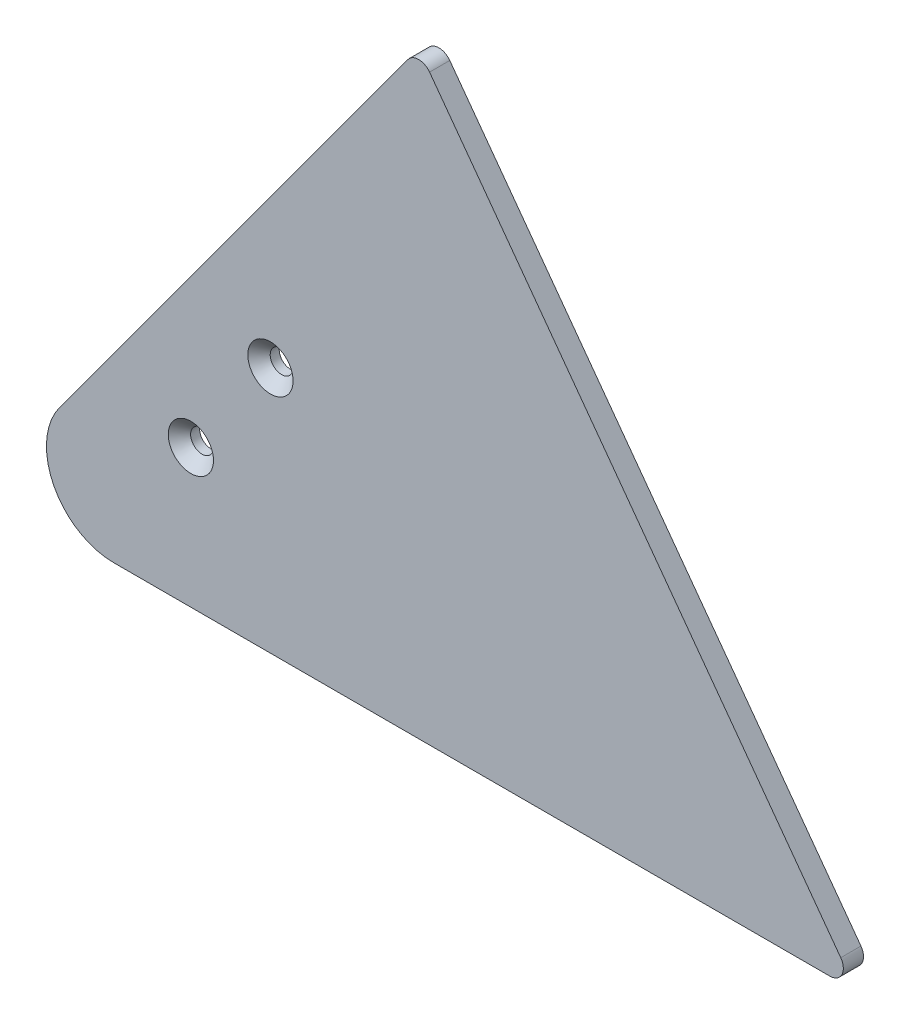
SolidWorks part; units mm, degrees
material "环氧树脂,未充填"
ref_plane "前视基准面" through (0, 0, 0) normal (0, 0, 1) x (1, 0, 0)
ref_plane "上视基准面" through (0, 0, 0) normal (0, 1, 0) x (1, 0, 0)
ref_plane "右视基准面" through (0, 0, 0) normal (1, 0, 0) x (0, 0, -1)
sketch "草图1" plane through (0, 0, 0) normal (0, 0, 1) x (1, 0, 0)
  line L0 (0, 0) -> (130, 0)
  line L1 (130, 0) -> (65, 88.7412)
  line L2 (65, 88.7412) -> (0, 0)
  dimension "D1" = 130
  dimension "D2" = 110
  dimension "D3" = 110
extrude "凸台-拉伸1" add sketch "草图1" along normal blind 3
sketch "草图2" plane through (0, 0, 3) normal (0, 0, 1) x (1, 0, 0)
  line L0 (73.0571, 77.7412) -> (16.1143, 0) construction
  line L1 (130, 0) -> (65, 88.7412) construction
  line L2 (0, 0) -> (130, 0) construction
  line L3 (65, 88.7412) -> (0, 0) construction
  line L4 (37.0785, 28.6214) -> (26.5909, 36.3032) construction
  circle A0 centre (42.9876, 36.6888) radius 1.5
  circle A2 centre (31.1694, 20.554) radius 1.5
  dimension "D3" = 3
  dimension "D1" = 13
  dimension "D2" = 45
  dimension "D4" = 10
extrude "切除-拉伸1" cut sketch "草图2" against normal through all
fillet "圆角1" radius 10 1 edges at (0, 0, 1.5)
fillet "圆角2" radius 2 2 edges at (65, 88.7412, 1.5) (130, 0, 1.5)
hole_wizard "M3 六角凹锥坑螺钉的锥形沉头孔1" positions "3D草图1" profile "草图6" countersink size "M3" standard "ISO" end condition through all
sketch3d "3D草图1"
  line L0 (42.9876, 36.6888, 0) -> (42.9876, 36.6888, 3) construction
  line L1 (31.1694, 20.554, 0) -> (31.1694, 20.554, 3) construction
  point P0 (42.9876, 36.6888, 3)
  point P4 (31.1694, 20.554, 3)
sketch "草图6" plane through (42.9876, 36.6888, 3) normal (1, 0, 0) x (0, -1, 0)
  line L0 (0, 0) -> (0, 3)
  line L1 (0, 3) -> (1.7, 3)
  line L2 (1.7, 3) -> (1.7, 1.66)
  line L3 (1.7, 1.66) -> (3.36, 0)
  line L5 (3.36, 0) -> (0, 0)
  line L6 (-1.7, 1.66) -> (-3.36, 0) construction
  line L11 (0, -6.35) -> (0, 107.95) construction
  dimension "通孔孔直径" = 3.4
  dimension "通孔孔深度" = 3
  dimension "近端锥形沉头孔直径" = 6.72
  dimension "近端锥形沉头孔角度" = 90
